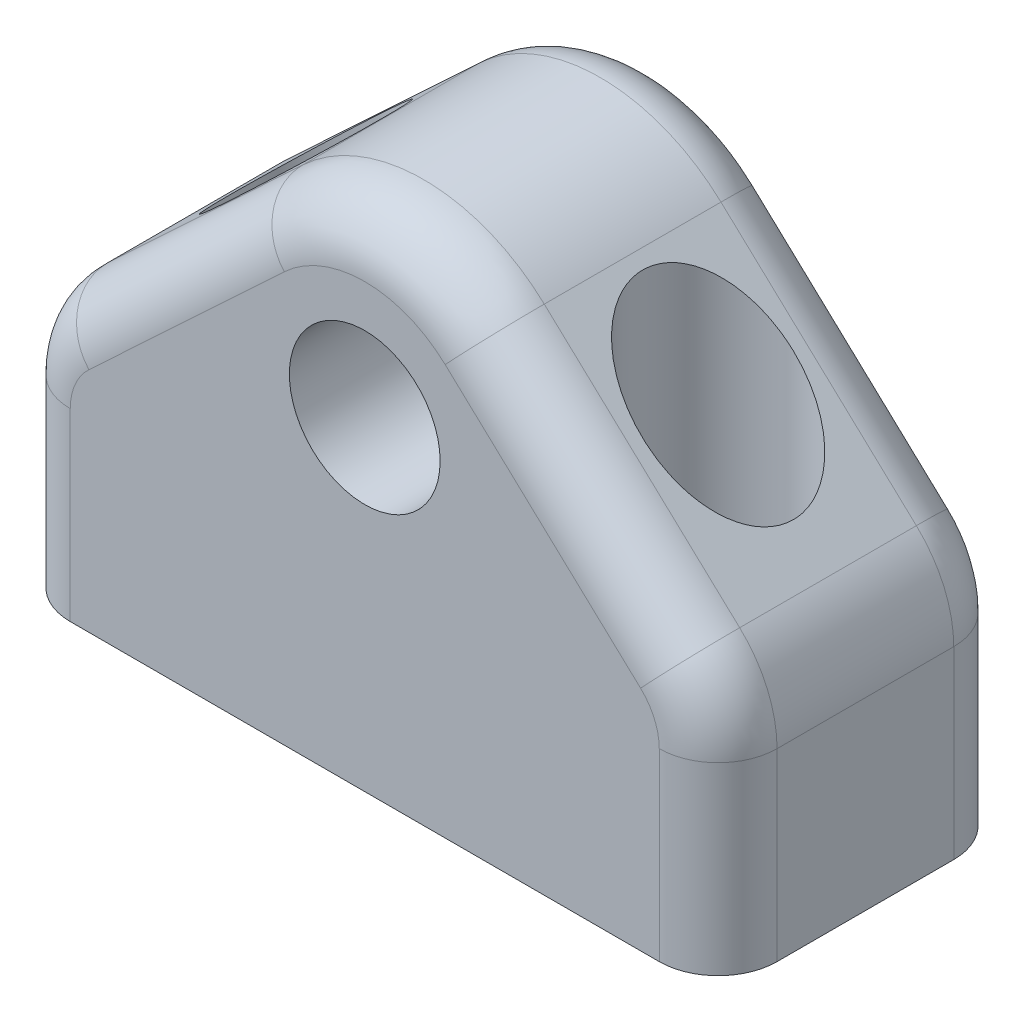
SolidWorks part; units mm, degrees
ref_plane "Front Plane" through (0, 0, 0) normal (0, 0, 1) x (1, 0, 0)
ref_plane "Top Plane" through (0, 0, 0) normal (0, 1, 0) x (1, 0, 0)
ref_plane "Right Plane" through (0, 0, 0) normal (1, 0, 0) x (0, 0, -1)
sketch "Sketch1" plane through (0, 0, 0) normal (0, 0, 1) x (1, 0, 0)
  line L0 (0, 0) -> (0, 4.9712)
  line L1 (1.0075, 7.2913) -> (6.2737, 12.2113)
  line L2 (12.7763, 12.2113) -> (18.0425, 7.2913)
  line L3 (19.05, 4.9712) -> (19.05, 0)
  line L4 (19.05, 0) -> (0, 0)
  arc A0 (6.2737, 12.2113) -> (12.7763, 12.2113) centre (9.525, 8.7312) cw
  arc A1 (18.0425, 7.2913) -> (19.05, 4.9712) centre (15.875, 4.9712) cw
  arc A2 (0, 4.9712) -> (1.0075, 7.2913) centre (3.175, 4.9712) cw
  circle A3 centre (9.525, 8.7312) radius 2.032
  point P13 (0, 6.35)
  dimension "D1" = 4.7625
  dimension "D5" = 3.175
  dimension "D6" = 4.064
  dimension "D2" = 19.05
  dimension "D3" = 6.35
  dimension "D4" = 8.7312
extrude "Boss-Extrude1" add sketch "Sketch1" along normal blind 7.9375
sketch "Sketch2" plane through (0, 0, 0) normal (0, -1, 0) x (1, 0, 0)
  line L0 (0, 7.9375) -> (0, 0) construction
  line L1 (0, 3.9688) -> (3.9688, 3.9688) construction
  line L2 (3.9688, 3.9688) -> (15.0812, 3.9688) construction
  line L3 (15.0812, 3.9688) -> (19.05, 3.9688) construction
  line L4 (19.05, 7.9375) -> (19.05, 0) construction
  circle A0 centre (3.9688, 3.9688) radius 2.032
  circle A1 centre (15.0812, 3.9688) radius 2.032
  point P7 (0, 3.9688)
  dimension "D1" = 4.064
  dimension "D2" = 11.1125
extrude "Cut-Extrude1" cut sketch "Sketch2" against normal through all
fillet "Fillet1" radius 1.5875 14 edges at (19.05, 2.4856, 0) (18.7873, 6.2359, 0) (15.4094, 9.7513, 0) (0, 2.4856, 0) (0.2627, 6.2359, 0) (3.6406, 9.7513, 0) (19.05, 2.4856, 7.9375) (18.7873, 6.2359, 7.9375) (15.4094, 9.7513, 7.9375) (0, 2.4856, 7.9375) (0.2627, 6.2359, 7.9375) (3.6406, 9.7513, 7.9375) (9.525, 13.4937, 0) (9.525, 13.4937, 7.9375)
